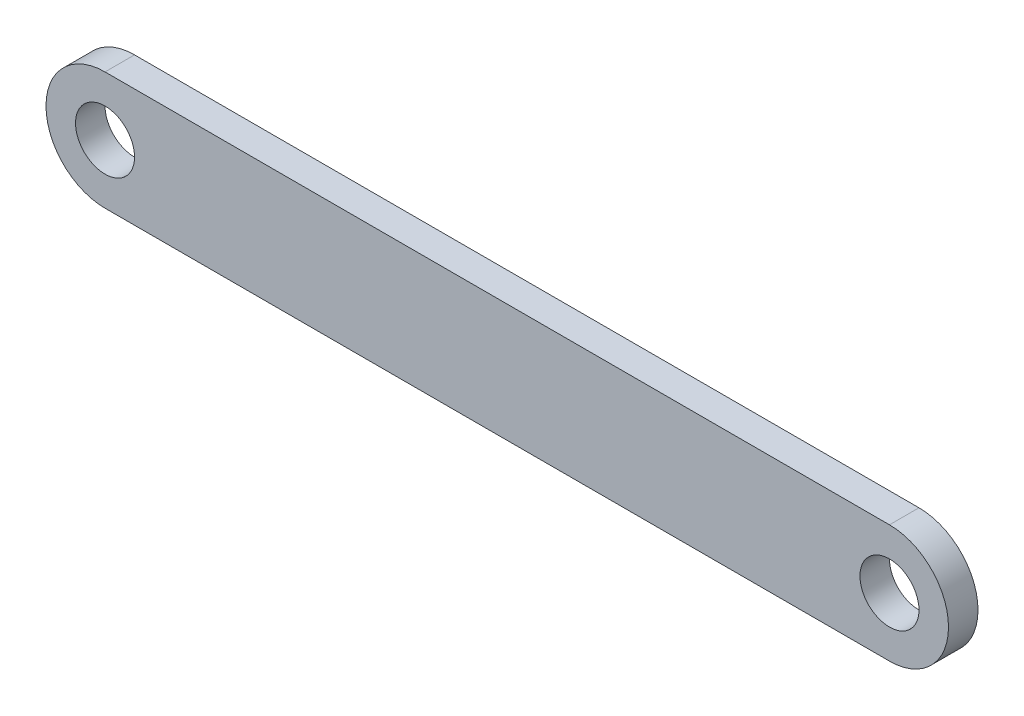
SolidWorks part; units mm, degrees
ref_plane "Спереди" through (0, 0, 0) normal (0, 0, 1) x (1, 0, 0)
ref_plane "Сверху" through (0, 0, 0) normal (0, 1, 0) x (1, 0, 0)
ref_plane "Справа" through (0, 0, 0) normal (1, 0, 0) x (0, 0, -1)
sketch "Sketch1" plane through (0, 0, 0) normal (0, 0, 1) x (1, 0, 0)
  line L0 (0, 0) -> (26.58, 0)
  line L1 (0, 2) -> (26.58, 2)
  line L2 (0, -2) -> (26.58, -2)
  circle A0 centre (0, 0) radius 1
  circle A1 centre (26.58, 0) radius 1
  circle A2 centre (0, 0) radius 2
  circle A3 centre (26.58, 0) radius 2
  dimension "D1" = 26.58
extrude "Extrude1" add sketch "Sketch1" against normal blind 1
